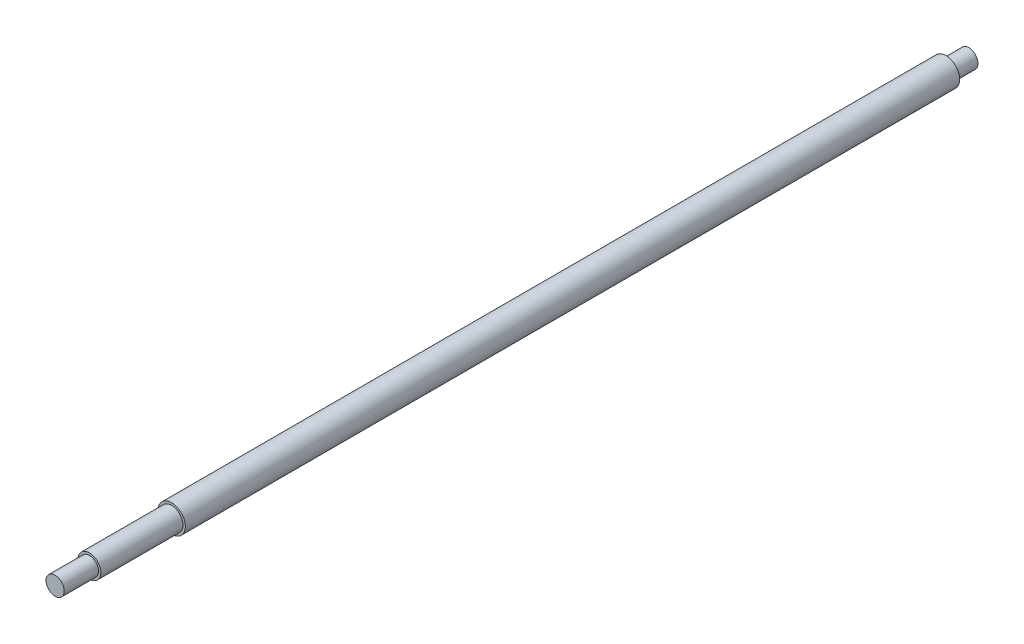
SolidWorks part; units mm, degrees
material "Хромистая нержавеющая сталь"
ref_plane "Спереди" through (0, 0, 0) normal (0, 0, 1) x (1, 0, 0)
ref_plane "Сверху" through (0, 0, 0) normal (0, 1, 0) x (1, 0, 0)
ref_plane "Справа" through (0, 0, 0) normal (1, 0, 0) x (0, 0, -1)
sketch "Эскиз1" plane through (0, 0, 0) normal (0, 0, 1) x (1, 0, 0)
  circle A0 centre (0, 0) radius 6
extrude "Бобышка-Вытянуть1" add sketch "Эскиз1" along normal blind 400
sketch "Эскиз2" plane through (0, 0, 400) normal (0, 0, 1) x (1, 0, 0)
  circle A0 centre (0, 0) radius 5
extrude "Вырез-Вытянуть1" cut sketch "Эскиз2" against normal blind 51 flip side to cut
sketch "Эскиз4" plane through (0, 0, 400) normal (0, 0, 1) x (1, 0, 0)
  circle A0 centre (0, 0) radius 4
extrude "Вырез-Вытянуть3" cut sketch "Эскиз4" against normal blind 15 flip side to cut
sketch "Эскиз5" plane through (0, 0, 0) normal (0, 0, -1) x (-1, 0, 0)
  circle A0 centre (0, 0) radius 4
extrude "Вырез-Вытянуть4" cut sketch "Эскиз5" against normal blind 10 flip side to cut
